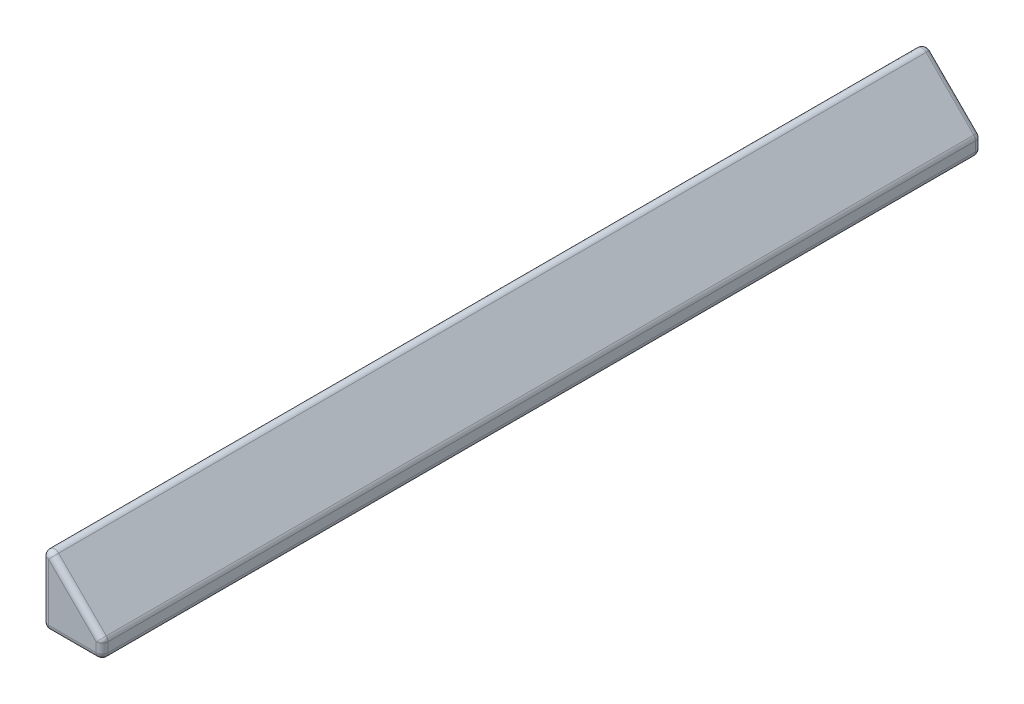
SolidWorks part; units mm, degrees
material "6061-T6 (SS)"
ref_plane "Front Plane" through (0, 0, 0) normal (0, 0, 1) x (1, 0, 0)
ref_plane "Top Plane" through (0, 0, 0) normal (0, 1, 0) x (1, 0, 0)
ref_plane "Right Plane" through (0, 0, 0) normal (1, 0, 0) x (0, 0, -1)
sketch "Sketch1" plane through (0, 0, 0) normal (0, 0, 1) x (1, 0, 0)
  line L5 (220, 0) -> (222.6, 0)
  line L6 (222.6, 0) -> (220, 2.6)
  line L7 (220, 2.6) -> (220, 0)
  line L8 (222.6, 0) -> (222.6, 2.6) construction
  line L9 (220, 2.6) -> (222.6, 2.6) construction
  line L10 (222.6, 2.6) -> (226.4, 2.6) construction
  line L11 (222, 0) -> (222, 0.6)
  dimension "D1" = 0.6
extrude "Boss-Extrude1" add sketch "Sketch1" against normal up to surface (13.1842 mm away) and the other way up to surface (16.3158 mm away) contours L5 L11 L6 L7
fillet "Fillet1" radius 0.2 12 edges at (221, 0, -13.1842) (221, 0, 16.3158) (220, 2.6, 1.5658) (220, 0, 1.5658) (221, 1.6, -13.1842) (220, 1.3, -13.1842) (221, 1.6, 16.3158) (220, 1.3, 16.3158) (222, 0.3, -13.1842) (222, 0.6, 1.5658) (222, 0, 1.5658) (222, 0.3, 16.3158)
